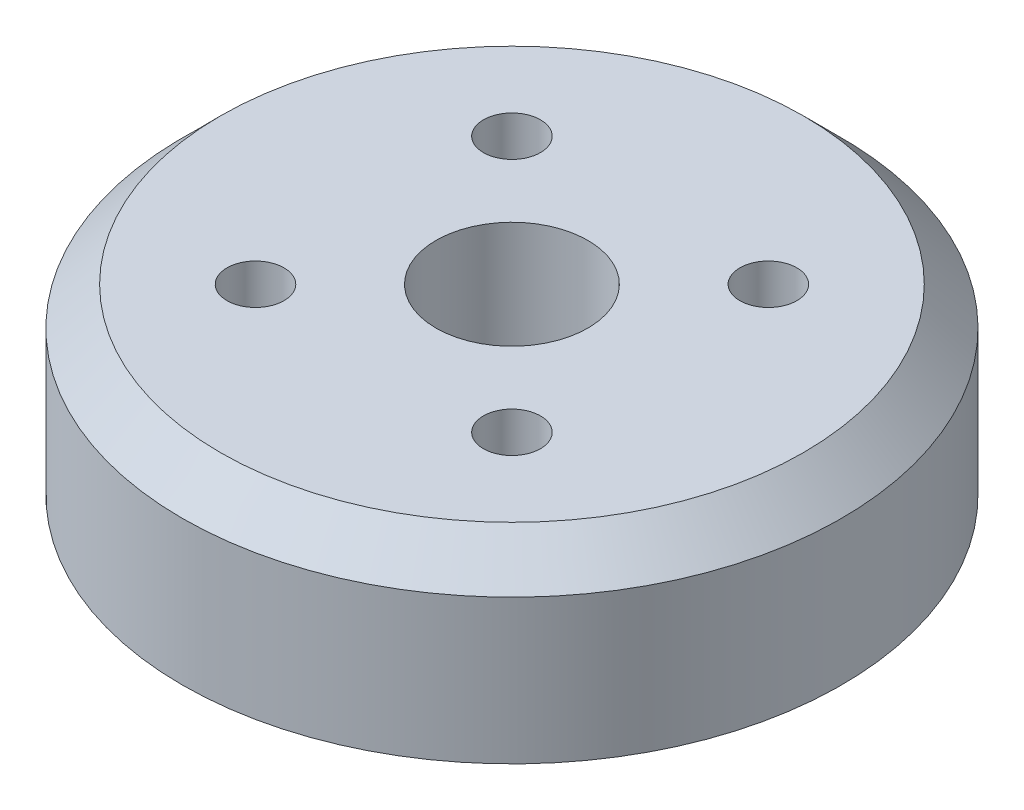
SolidWorks part; units mm, degrees
material "AA380.0-F 锻模"
ref_plane "前视基准面" through (0, 0, 0) normal (0, 0, 1) x (1, 0, 0)
ref_plane "上视基准面" through (0, 0, 0) normal (0, 1, 0) x (1, 0, 0)
ref_plane "右视基准面" through (0, 0, 0) normal (1, 0, 0) x (0, 0, -1)
sketch "草图1" plane through (0, 0, 0) normal (0, 1, 0) x (1, 0, 0)
  circle A0 centre (0, 0) radius 17.35
  dimension "D1" = 34.7
extrude "凸台-拉伸1" add sketch "草图1" along normal blind 9.6
chamfer "倒角1" distance 2 angle 45 1 edges at (0, 9.6, 17.35)
sketch "草图2" plane through (0, 9.6, 0) normal (0, 1, 0) x (1, 0, 0)
  line L1 (-6.75, 6.75) -> (6.75, 6.75)
  line L2 (-6.75, 6.75) -> (-6.75, -6.75)
  line L3 (-6.75, -6.75) -> (6.75, -6.75)
  line L4 (6.75, 6.75) -> (6.75, -6.75)
  line L5 (-6.75, 6.75) -> (6.75, -6.75) construction
  line L6 (-6.75, -6.75) -> (6.75, 6.75) construction
  circle A0 centre (0, 0) radius 4
  circle A1 centre (-6.75, 6.75) radius 1.5
  circle A2 centre (6.75, 6.75) radius 1.5
  circle A3 centre (6.75, -6.75) radius 1.5
  circle A4 centre (-6.75, -6.75) radius 1.5
  point P17 (0, 0)
  dimension "D1" = 8
  dimension "D4" = 3
  dimension "D2" = 13.5
  dimension "D3" = 13.5
  dimension "D5" = 4
extrude "切除-拉伸1" cut sketch "草图2" against normal blind 9.6 contours A1 | A2 | A3 | A4 | A0
